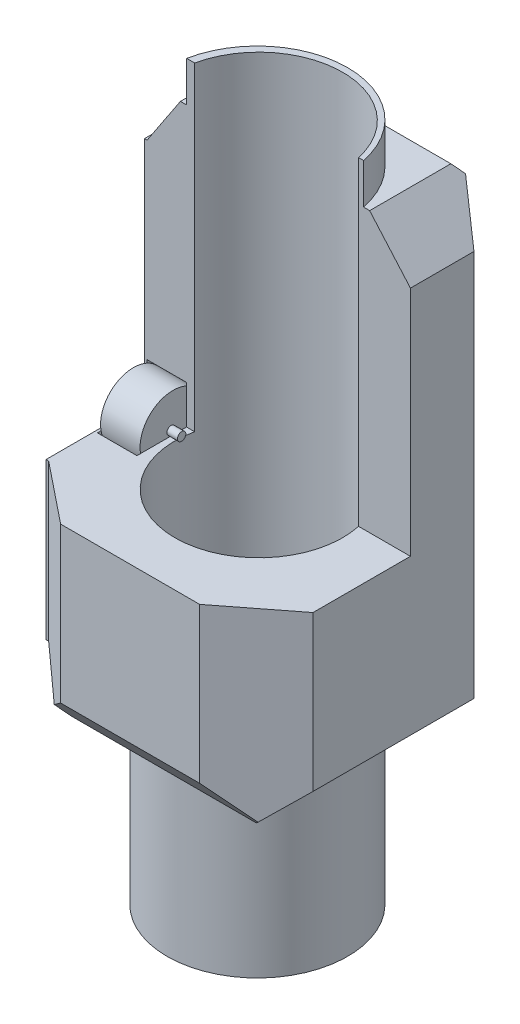
SolidWorks part; units mm, degrees
ref_plane "Front Plane" through (0, 0, 0) normal (0, 0, 1) x (1, 0, 0)
ref_plane "Top Plane" through (0, 0, 0) normal (0, 1, 0) x (1, 0, 0)
ref_plane "Right Plane" through (0, 0, 0) normal (1, 0, 0) x (0, 0, -1)
sketch "Sketch1" plane through (0, 0, 0) normal (0, 1, 0) x (1, 0, 0)
  line L1 (0, 0) -> (-100, 0)
  line L2 (0, 0) -> (0, 100)
  line L3 (0, 100) -> (-100, 100)
  line L4 (-100, 0) -> (-100, 100)
  dimension "D1" = 100
  dimension "D2" = 100
extrude "Boss-Extrude1" add sketch "Sketch1" along normal blind 180
sketch "Sketch2" plane through (0, 180, 0) normal (0, 1, 0) x (1, 0, 0)
  circle A0 centre (-51.3773, 49.0765) radius 34.2578
extrude "Boss-Extrude2" add sketch "Sketch2" along normal mid plane 700
sketch "Sketch3" plane through (0, 0, 0) normal (1, 0, 0) x (0, 0, -1)
  line L1 (-18.5833, 361.0481) -> (133.4231, 361.0481)
  line L2 (-18.5833, 361.0481) -> (-18.5833, 643.5005)
  line L3 (-18.5833, 643.5005) -> (133.4231, 643.5005)
  line L4 (133.4231, 361.0481) -> (133.4231, 643.5005)
extrude "Cut-Extrude2" cut sketch "Sketch3" against normal blind 400
sketch "Sketch4" plane through (0, 0, 0) normal (1, 0, 0) x (0, 0, -1)
  line L0 (12.982, 0) -> (-8.9942, 25.8281)
  line L1 (-8.9942, 25.8281) -> (-18.5645, -15.2595)
  line L2 (-18.5645, -15.2595) -> (12.982, 0)
  line L3 (85.0725, -1.4481) -> (109.2376, 19.1131)
  line L4 (109.2376, 19.1131) -> (115.92, -3.2674)
  line L5 (115.92, -3.2674) -> (85.0725, -1.4481)
  line L6 (12.982, 180) -> (-8.9942, 148.5376)
  line L7 (-8.9942, 148.5376) -> (-15.4182, 193.2193)
  line L8 (-15.4182, 193.2193) -> (12.982, 180)
  line L9 (85.0725, 181.8543) -> (103.8412, 159.7959)
  line L10 (103.8412, 159.7959) -> (106.1325, 198.6474)
  line L11 (106.1325, 198.6474) -> (85.0725, 181.8543)
extrude "Cut-Extrude3" cut sketch "Sketch4" against normal blind 400
sketch "Sketch5" plane through (0, 0, 0) normal (0, 0, 1) x (1, 0, 0)
  line L0 (-85.6233, 0) -> (-106.3704, 21.4264)
  line L1 (-106.3704, 21.4264) -> (-122.2889, 3.2093)
  line L2 (-122.2889, 3.2093) -> (-93.5263, -19.8847)
  line L3 (-93.5263, -19.8847) -> (-85.6233, 0)
  line L4 (-15.695, 0) -> (0, 15.2574)
  line L5 (0, 15.2574) -> (12.1227, 15.2574)
  line L6 (12.1227, 15.2574) -> (10.5631, -19.8847)
  line L7 (10.5631, -19.8847) -> (-15.695, 0)
  line L8 (-87.1665, 180.2481) -> (-106.3704, 151.2911)
  line L9 (-106.3704, 151.2911) -> (-117.7055, 200.5011)
  line L10 (-117.7055, 200.5011) -> (-87.1665, 180.2481)
  line L11 (-15.695, 180.2481) -> (7.8338, 153.2796)
  line L12 (7.8338, 153.2796) -> (0, 193.9412)
  line L13 (0, 193.9412) -> (-15.695, 180.2481)
extrude "Cut-Extrude4" cut sketch "Sketch5" against normal blind 400
sketch "Sketch6" plane through (0, 180, 0) normal (0, 1, 0) x (1, 0, 0)
  line L1 (-112.387, 28.4004) -> (-64.2613, -10.2128)
  line L2 (-112.387, 28.4004) -> (-124.6497, -15.5119)
  line L3 (-124.6497, -15.5119) -> (-84.4064, -15.5119)
  line L4 (-64.2613, -10.2128) -> (-84.4064, -15.5119)
  line L5 (-97.0655, 135.8618) -> (-119.3755, 77.7927)
  line L6 (-97.0655, 135.8618) -> (-66.4287, 110.5752)
  line L7 (-66.4287, 110.5752) -> (-118.0433, 64.3476)
  line L8 (-119.3755, 77.7927) -> (-118.0433, 64.3476)
  line L9 (-24.6964, -21.8158) -> (11.0921, -8.9736)
  line L10 (-24.6964, -21.8158) -> (-38.5316, -11.1392)
  line L11 (-38.5316, -11.1392) -> (17.4283, 32.3938)
  line L12 (11.0921, -8.9736) -> (17.4283, 32.3938)
  line L13 (-17.4455, 140.8044) -> (35.4175, 107.2625)
  line L14 (-17.4455, 140.8044) -> (-31.7244, 103.6253)
  line L15 (-31.7244, 103.6253) -> (9.3055, 72.9964)
  line L16 (35.4175, 107.2625) -> (9.3055, 72.9964)
extrude "Cut-Extrude5" cut sketch "Sketch6" against normal blind 400
sketch "Sketch7" plane through (0, 0, 0) normal (0, 0, 1) x (1, 0, 0)
  line L1 (-146.2029, -210.0437) -> (13.9564, -210.0437)
  line L2 (-146.2029, -210.0437) -> (-146.2029, -62.6814)
  line L3 (-146.2029, -62.6814) -> (13.9564, -62.6814)
  line L4 (13.9564, -210.0437) -> (13.9564, -62.6814)
extrude "Cut-Extrude6" cut sketch "Sketch7" against normal blind 400
sketch "Sketch8" plane through (0, 0, 0) normal (0, 0, 1) x (1, 0, 0)
  line L1 (-127.1965, 251.4288) -> (20.1142, 251.4288)
  line L2 (-127.1965, 251.4288) -> (-127.1965, 413.4677)
  line L3 (-127.1965, 413.4677) -> (20.1142, 413.4677)
  line L4 (20.1142, 251.4288) -> (20.1142, 413.4677)
extrude "Cut-Extrude7" cut sketch "Sketch8" against normal blind 400
sketch "Sketch9" plane through (0, 251.4288, 0) normal (0, 1, 0) x (1, 0, 0)
  circle A0 centre (-50.809, 49.032) radius 31.8473
extrude "Cut-Extrude8" cut sketch "Sketch9" against normal blind 400
sketch "Sketch10" plane through (-100, 0, 0) normal (-1, 0, 0) x (0, 0, 1)
  line L1 (-55.8114, 74.0839) -> (84.4096, 74.0839)
  line L2 (-55.8114, 74.0839) -> (-55.8114, 286.1174)
  line L3 (-55.8114, 286.1174) -> (84.4096, 286.1174)
  line L4 (84.4096, 74.0839) -> (84.4096, 286.1174)
extrude "Cut-Extrude9" cut sketch "Sketch10" against normal blind 400
sketch "Sketch11" plane through (-100, 0, 0) normal (-1, 0, 0) x (0, 0, 1)
  circle A0 centre (-50.4133, 76.2646) radius 13.6031
extrude "Cut-Extrude11" cut sketch "Sketch11" against normal blind 15
sketch "Sketch12" plane through (-85, 0, 0) normal (-1, 0, 0) x (0, 0, 1)
  circle A0 centre (-50.6588, 76.2225) radius 12.4954
extrude "Boss-Extrude3" add sketch "Sketch12" along normal blind 15
sketch "Sketch13" plane through (-85, 0, 0) normal (1, 0, 0) x (0, 0, -1)
  circle A0 centre (49.9452, 75.9448) radius 1.5949
extrude "Boss-Extrude4" add sketch "Sketch13" along normal blind 4
sketch "Sketch14" plane through (-100, 0, 0) normal (-1, 0, 0) x (0, 0, 1)
  line L1 (-115.7243, 195.3259) -> (-14.9757, 195.3259)
  line L2 (-115.7243, 195.3259) -> (-115.7243, 305.8809)
  line L3 (-115.7243, 305.8809) -> (-14.9757, 305.8809)
  line L4 (-14.9757, 195.3259) -> (-14.9757, 305.8809)
extrude "Cut-Extrude13" cut sketch "Sketch14" against normal blind 400
sketch "Sketch15" plane through (-100, 0, 0) normal (-1, 0, 0) x (0, 0, 1)
  line L0 (-18.4618, 14.8474) -> (-80.5077, 14.8474)
  line L1 (-80.5077, 14.8474) -> (-80.5077, 160.8968)
  line L2 (-80.5077, 160.8968) -> (-55.8114, 160.8968)
  line L3 (-55.8114, 160.8968) -> (-55.8114, 74.0839)
  line L4 (-55.8114, 74.0839) -> (-18.4618, 74.0839)
  line L5 (-18.4618, 74.0839) -> (-18.4618, 14.8474)
extrude "Boss-Extrude5" add sketch "Sketch15" along normal blind 1
sketch "Sketch16" plane through (-101, 0, 0) normal (-1, 0, 0) x (0, 0, 1)
  line L1 (-69.1316, 29.9073) -> (-27.023, 29.9073)
  line L2 (-69.1316, 29.9073) -> (-69.1316, 60.3656)
  line L3 (-69.1316, 60.3656) -> (-27.023, 60.3656)
  line L4 (-27.023, 29.9073) -> (-27.023, 60.3656)
extrude "Boss-Extrude6" add sketch "Sketch16" along normal blind 5
sketch "Sketch17" plane through (-101, 0, 0) normal (-1, 0, 0) x (0, 0, 1)
  line L1 (-76.3814, 119.2079) -> (-57.7119, 119.2079)
  line L2 (-76.3814, 119.2079) -> (-76.3814, 141.6106)
  line L3 (-76.3814, 141.6106) -> (-57.7119, 141.6106)
  line L4 (-57.7119, 119.2079) -> (-57.7119, 141.6106)
extrude "Boss-Extrude7" add sketch "Sketch17" along normal blind 1
sketch "Sketch18" plane through (-102, 0, 0) normal (-1, 0, 0) x (0, 0, 1)
  line L1 (-74.0789, 127.628) -> (-69.1713, 127.628)
  line L2 (-74.0789, 127.628) -> (-74.0789, 132.7988)
  line L3 (-74.0789, 132.7988) -> (-69.1713, 132.7988)
  line L4 (-69.1713, 127.628) -> (-69.1713, 132.7988)
  line L5 (-60.3069, 127.1415) -> (-64.2884, 127.1415)
  line L6 (-60.3069, 127.1415) -> (-60.3069, 132.5929)
  line L7 (-60.3069, 132.5929) -> (-64.2884, 132.5929)
  line L8 (-64.2884, 127.1415) -> (-64.2884, 132.5929)
extrude "Boss-Extrude8" add sketch "Sketch18" along normal blind 1
sketch "Sketch19" plane through (-102, 0, 0) normal (-1, 0, 0) x (0, 0, 1)
  line L0 (-66.9765, 134.8688) -> (-73.7929, 134.8688)
  line L1 (-73.7929, 134.8688) -> (-73.7929, 134.1083)
  line L2 (-73.7929, 134.1083) -> (-74.5719, 134.1083)
  line L3 (-74.5719, 134.1083) -> (-74.5719, 140.5127)
  line L4 (-74.5719, 140.5127) -> (-73.7929, 140.5127)
  line L5 (-73.7929, 140.5127) -> (-72.166, 140.5127)
  line L6 (-66.9765, 134.8688) -> (-66.9765, 135.4972)
  line L7 (-66.9765, 135.4972) -> (-73.7929, 135.4233)
  line L8 (-73.7929, 135.4233) -> (-73.7929, 139.5456)
  line L9 (-73.7929, 139.5456) -> (-72.9212, 139.5456)
  line L10 (-72.9212, 139.5456) -> (-72.9212, 136.6931)
  line L11 (-72.166, 140.5127) -> (-72.2334, 137.4219)
  line L12 (-72.9212, 136.6931) -> (-70.7839, 136.6931)
  line L13 (-72.2334, 137.4219) -> (-71.4846, 137.4219)
  line L14 (-71.4846, 137.4219) -> (-71.4109, 140.5127)
  line L15 (-71.4109, 140.5127) -> (-69.1583, 140.5049)
  line L16 (-70.7839, 136.6931) -> (-70.7097, 139.9027)
  line L17 (-70.7097, 139.9027) -> (-70.0087, 139.9027)
  line L18 (-69.1583, 140.5049) -> (-69.1583, 137.4219)
  line L19 (-70.0087, 139.9027) -> (-70.0087, 136.6677)
  line L20 (-70.0087, 136.6677) -> (-67.49, 136.6677)
  line L21 (-69.1583, 137.4219) -> (-68.2217, 137.4219)
  line L22 (-67.49, 136.6677) -> (-67.49, 139.9027)
  line L23 (-67.49, 139.9027) -> (-66.3346, 139.9027)
  line L24 (-66.3346, 139.9027) -> (-66.3346, 136.6677)
  line L25 (-68.2217, 137.4219) -> (-68.2217, 140.5679)
  line L26 (-68.2217, 140.5679) -> (-65.4269, 140.5679)
  line L27 (-65.4269, 140.5679) -> (-65.5152, 137.4462)
  line L28 (-66.3346, 136.6677) -> (-64.0048, 136.6677)
  line L29 (-64.0048, 136.6677) -> (-64.0048, 139.9797)
  line L30 (-64.0048, 139.9797) -> (-63.0901, 139.9797)
  line L31 (-63.0901, 139.9797) -> (-63.0901, 136.6677)
  line L32 (-63.0901, 136.6677) -> (-60.6958, 136.6677)
  line L33 (-60.6958, 136.6677) -> (-60.6958, 139.9841)
  line L34 (-60.6958, 139.9841) -> (-59.6983, 139.9949)
  line L35 (-65.5152, 137.4462) -> (-64.7141, 137.4462)
  line L36 (-64.7141, 137.4462) -> (-64.7141, 140.5679)
  line L37 (-64.7141, 140.5679) -> (-62.4109, 140.5679)
  line L38 (-62.4109, 140.5679) -> (-62.4109, 137.2101)
  line L39 (-62.4109, 137.2101) -> (-61.4035, 137.2101)
  line L40 (-61.4035, 137.2101) -> (-61.4035, 140.6311)
  line L41 (-61.4035, 140.6311) -> (-58.89, 140.6311)
  line L42 (-58.89, 140.6311) -> (-58.89, 136.5955)
  line L43 (-58.89, 136.5955) -> (-59.6983, 136.5955)
  line L44 (-59.6983, 136.5955) -> (-59.6983, 139.9949)
extrude "Cut-Extrude14" cut sketch "Sketch19" against normal blind 2 contours L12 L16 L17 L19 L20 L22 L23 L24 L28 L29 L30 L31 L32 L33 L34 L44 L43 L42 L41 L40 L39 L38 L37 L36 L35 L27 L26 L25 L21 L18 L15 L14 L13 L11 L5 L4 L3 L2 L1 L0 L6 L7 L8 L9 L10
